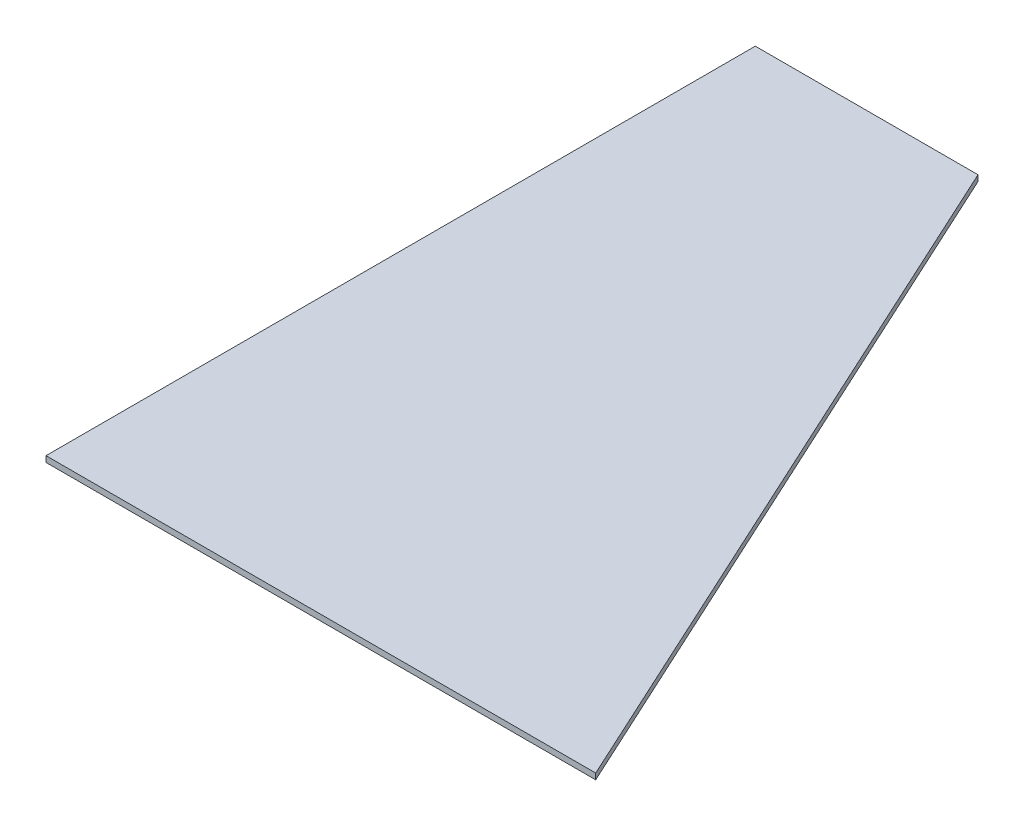
SolidWorks part; units mm, degrees
ref_plane "Front Plane" through (0, 0, 0) normal (0, 0, 1) x (1, 0, 0)
ref_plane "Top Plane" through (0, 0, 0) normal (0, 1, 0) x (1, 0, 0)
ref_plane "Right Plane" through (0, 0, 0) normal (1, 0, 0) x (0, 0, -1)
sketch "Sketch1" plane through (0, 0, 0) normal (0, 1, 0) x (1, 0, 0)
  line L0 (0, 0) -> (590.55, 0)
  line L1 (590.55, 0) -> (239.2632, 762)
  line L2 (239.2632, 762) -> (0, 762)
  line L3 (0, 762) -> (0, 0)
  dimension "D1" = 590.55
  dimension "D2" = 762
  dimension "D3" = 65.25
extrude "Boss-Extrude1" add sketch "Sketch1" along normal blind 6.35
sketch "Strut outline" plane through (0, 6.35, 0) normal (0, 1, 0) x (1, 0, 0)
  line L0 (44.45, 0) -> (44.45, 762)
  line L1 (44.45, 0) -> (-44.45, 0)
  line L2 (44.45, 762) -> (-44.45, 762)
  line L3 (-44.45, 0) -> (-44.45, 762)
  line L4 (0, 0) -> (590.55, 0) construction
  line L5 (239.2632, 762) -> (0, 762) construction
  point P8 (0, 762)
  dimension "D1" = 88.9
sketch "Sketch3" [suppressed] plane through (0, 6.35, 0) normal (0, 1, 0) x (1, 0, 0)
  line L0 (127, 330.2) -> (203.2, 330.2) construction
  line L1 (82.55, 304.8) -> (171.45, 304.8) construction
  line L2 (82.55, 304.8) -> (82.55, 381) construction
  line L3 (82.55, 381) -> (171.45, 381) construction
  line L4 (171.45, 304.8) -> (171.45, 381) construction
  line L5 (95.25, 479.425) -> (158.75, 479.425) construction
  line L6 (95.25, 479.425) -> (95.25, 536.575) construction
  line L7 (95.25, 536.575) -> (158.75, 536.575) construction
  line L8 (158.75, 479.425) -> (158.75, 536.575) construction
  line L9 (95.25, 479.425) -> (158.75, 536.575) construction
  line L10 (95.25, 536.575) -> (158.75, 479.425) construction
  line L11 (203.2, 311.15) -> (203.2, 349.25) construction
  line L12 (127, 508) -> (203.2, 508) construction
  line L13 (203.2, 488.95) -> (203.2, 527.05) construction
  line L14 (0, 762) -> (0, 0) construction
  line L15 (-50.8, 679.45) -> (37.3063, 679.45)
  line L16 (-50.8, 679.45) -> (-50.8, 685.8)
  line L17 (-50.8, 685.8) -> (50.8, 685.8)
  line L18 (50.8, 679.45) -> (50.8, 685.8)
  line L19 (-50.8, 679.45) -> (50.8, 685.8) construction
  line L20 (-50.8, 685.8) -> (38.0326, 680.248) construction
  line L21 (38.0326, 680.248) -> (50.8, 679.45) construction
  line L22 (42.0687, 679.45) -> (50.8, 679.45)
  line L23 (50.8, 679.45) -> (50.8, 609.6) construction
  line L24 (50.8, 609.6) -> (-50.8, 609.6) construction
  line L25 (-50.8, 609.6) -> (-50.8, 679.45) construction
  line L26 (63.5, 120.65) -> (114.3, 120.65) construction
  line L27 (165.1, 158.75) -> (215.9, 158.75) construction
  line L29 (165.1, 120.65) -> (165.1, 158.75) construction
  line L30 (590.55, 0) -> (239.2632, 762) construction
  line L31 (366.1278, 304.8) -> (302.3241, 443.201) construction
  circle A0 centre (127, 330.2) radius 25.4
  circle A1 centre (127, 508) radius 25.4
  circle A2 centre (203.2, 311.15) radius 3.81
  circle A3 centre (203.2, 349.25) radius 2.667
  circle A4 centre (203.2, 488.95) radius 3.81
  circle A5 centre (203.2, 527.05) radius 2.667
  circle A6 centre (381, 139.7) radius 36.5125
  arc A7 (37.3063, 679.45) -> (42.0687, 679.45) centre (39.6875, 676.275) ccw
  circle A8 centre (63.5, 120.65) radius 3.81
  circle A9 centre (114.3, 120.65) radius 3.81
  circle A10 centre (165.1, 120.65) radius 3.81
  circle A11 centre (215.9, 120.65) radius 3.81
  circle A12 centre (266.7, 120.65) radius 3.81
  circle A13 centre (165.1, 158.75) radius 2.667
  circle A14 centre (215.9, 158.75) radius 2.667
  circle A15 centre (266.7, 158.75) radius 2.667
  circle A18 centre (63.5, 158.75) radius 2.667
  circle A19 centre (114.3, 158.75) radius 2.667
  circle A21 centre (366.1278, 304.8) radius 25.4
  circle A22 centre (302.3241, 443.201) radius 25.4
  point P6 (127, 304.8)
  point P21 (0, 682.625)
  point P25 (203.2, 330.2)
  point P29 (203.2, 508)
  point P37 (0, 609.6)
  dimension "D1" = 50.8
  dimension "D4" = 50.8
  dimension "D7" = 7.62
  dimension "D8" = 5.334
  dimension "D11" = 73.025
  dimension "D14" = 7.9375
  dimension "D24" = 7.62
  dimension "D29" = 5.334
  dimension "D35" = 50.8
  dimension "D2" = 88.9
  dimension "D3" = 76.2
  dimension "D5" = 63.5
  dimension "D6" = 57.15
  dimension "D9" = 38.1
  dimension "D10" = 76.2
  dimension "D12" = 101.6
  dimension "D13" = 6.35
  dimension "D15" = 11.1125
  dimension "D16" = 9.525
  dimension "D17" = 76.2
  dimension "D18" = 177.8
  dimension "D19" = 127
  dimension "D20" = 330.2
  dimension "D21" = 609.6
  dimension "D22" = 381
  dimension "D23" = 139.7
  dimension "D26" = 50.8
  dimension "D27" = 63.5
  dimension "D28" = 120.65
  dimension "D30" = 38.1
  dimension "D32" = 50.8
  dimension "D36" = 304.8
  dimension "D37" = 76.2
  dimension "D39" = 152.4
  dimension "D25" = 5
  dimension "D31" = 3
  dimension "D38" = 2
extrude "1st_doctor_left" [suppressed] cut sketch "Sketch3" against normal through all
sketch "Sketch4" [suppressed] plane through (0, 0, 0) normal (0, -1, 0) x (1, 0, 0)
  line L0 (317.5, -139.7) -> (348.4933, -70.0878) construction
  line L1 (317.5, -139.7) -> (317.5, 0) construction
  line L2 (0, 0) -> (590.55, 0) construction
  line L3 (317.5, -139.7) -> (348.4933, -70.0878) construction
  line L4 (317.5, -139.7) -> (374.1276, -88.7122) construction
  line L5 (88.9, -158.75) -> (88.9, -196.85) construction
  line L6 (88.9, -120.65) -> (139.7, -120.65) construction
  line L7 (0, -762) -> (0, 0) construction
  line L8 (50.8, -685.8) -> (-50.8, -685.8)
  line L9 (50.8, -685.8) -> (50.8, -679.45)
  line L10 (50.8, -679.45) -> (42.0688, -679.45)
  line L11 (-50.8, -685.8) -> (-50.8, -679.45)
  line L12 (50.8, -685.8) -> (-50.8, -679.45) construction
  line L13 (50.8, -679.45) -> (-50.8, -685.8) construction
  line L14 (50.8, -679.45) -> (50.8, -609.6) construction
  line L15 (50.8, -609.6) -> (-50.8, -609.6) construction
  line L16 (-50.8, -609.6) -> (-50.8, -679.45) construction
  line L17 (37.3063, -679.45) -> (-50.8, -679.45)
  line L18 (590.55, 0) -> (239.2632, -762) construction
  line L19 (366.1278, -304.8) -> (302.3241, -443.201) construction
  line L20 (139.7, -419.1) -> (139.7, -330.2) construction
  line L21 (203.2, -330.2) -> (76.2, -330.2) construction
  circle A0 centre (139.7, -419.1) radius 7.9375
  circle A1 centre (139.7, -419.1) radius 34.925 construction
  circle A2 centre (317.5, -139.7) radius 4.7625
  circle A3 centre (317.5, -139.7) radius 50.8 construction
  circle A4 centre (348.4933, -70.0878) radius 2.667
  circle A5 centre (374.1276, -88.7122) radius 2.667
  circle A6 centre (389.9705, -116.1529) radius 2.667
  circle A7 centre (393.2826, -147.6651) radius 2.667
  circle A8 centre (383.4911, -177.8) radius 2.667
  circle A9 centre (362.2892, -201.3471) radius 2.667
  circle A10 centre (333.3429, -214.2348) radius 2.667
  circle A11 centre (301.6571, -214.2348) radius 2.667
  circle A12 centre (272.7108, -201.3471) radius 2.667
  circle A13 centre (251.5089, -177.8) radius 2.667
  circle A14 centre (241.7174, -147.6651) radius 2.667
  circle A15 centre (245.0295, -116.1529) radius 2.667
  circle A16 centre (260.8724, -88.7122) radius 2.667
  circle A17 centre (286.5067, -70.0878) radius 2.667
  circle A18 centre (88.9, -120.65) radius 3.81
  circle A19 centre (88.9, -158.75) radius 2.667
  circle A20 centre (88.9, -196.85) radius 2.667
  arc A28 (42.0688, -679.45) -> (37.3063, -679.45) centre (39.6875, -676.275) ccw
  circle A29 centre (139.7, -120.65) radius 3.81
  circle A30 centre (139.7, -120.65) radius 3.81 [skipped]
  circle A31 centre (139.7, -158.75) radius 2.667 [skipped]
  circle A32 centre (139.7, -196.85) radius 2.667 [skipped]
  circle A33 centre (139.7, -158.75) radius 2.667
  circle A34 centre (139.7, -196.85) radius 2.667
  circle A39 centre (228.6, -584.2) radius 11.1125
  circle A40 centre (366.1278, -304.8) radius 25.4
  circle A41 centre (302.3241, -443.201) radius 25.4
  circle A42 centre (203.2, -330.2) radius 2.667
  circle A43 centre (139.7, -330.2) radius 2.667
  circle A44 centre (76.2, -330.2) radius 2.667
  point P40 (0, -682.625)
  point P87 (139.7, -330.2)
  dimension "D1" = 15.875
  dimension "D4" = 69.85
  dimension "D5" = 9.525
  dimension "D8" = 101.6
  dimension "D9" = 5.334
  dimension "D14" = 7.62
  dimension "D15" = 5.334
  dimension "D25" = 7.9375
  dimension "D33" = 76.2
  dimension "D36" = 22.225
  dimension "D31" = 50.8
  dimension "D35" = 5.334
  dimension "D2" = 139.7
  dimension "D3" = 419.1
  dimension "D6" = 317.5
  dimension "D7" = 139.7
  dimension "D10" = 24
  dimension "D12" = 24
  dimension "D13" = 76.2
  dimension "D16" = 38.1
  dimension "D17" = 120.65
  dimension "D18" = 88.9
  dimension "D20" = 38.1
  dimension "D22" = 2
  dimension "D23" = 101.6
  dimension "D24" = 6.35
  dimension "D26" = 11.1125
  dimension "D27" = 9.525
  dimension "D28" = 76.2
  dimension "D29" = 609.6
  dimension "D30" = 50.8
  dimension "D32" = 304.8
  dimension "D37" = 584.2
  dimension "D38" = 228.6
  dimension "D34" = 152.4
  dimension "D39" = 127
  dimension "D40" = 88.9
  dimension "D19" = 2
  dimension "D21" = 2
  dimension "D11" = 14
extrude "1st_doctor_right" [suppressed] cut sketch "Sketch4" against normal through all
sketch "Sketch5" [suppressed] plane through (0, 6.35, 0) normal (0, 1, 0) x (1, 0, 0)
  line L0 (0, 0) -> (590.55, 0) construction
  line L1 (590.55, 0) -> (239.2632, 762) construction
  line L2 (499.483, 76.2) -> (483.5321, 110.8003) construction
  circle A0 centre (499.483, 76.2) radius 3.937
  circle A1 centre (483.5321, 110.8003) radius 3.937
  circle A2 centre (467.5811, 145.4005) radius 3.937
  circle A3 centre (451.6302, 180.0008) radius 3.937
  circle A4 centre (435.6793, 214.601) radius 3.937
  circle A5 centre (419.7283, 249.2013) radius 3.937
  circle A6 centre (403.7774, 283.8015) radius 3.937
  circle A7 centre (387.8265, 318.4018) radius 3.937
  circle A8 centre (371.8755, 353.002) radius 3.937
  circle A9 centre (355.9246, 387.6023) radius 3.937
  circle A10 centre (339.9736, 422.2025) radius 3.937
  circle A11 centre (324.0227, 456.8028) radius 3.937
  circle A12 centre (308.0718, 491.4031) radius 3.937
  circle A13 centre (292.1208, 526.0033) radius 3.937
  circle A14 centre (276.1699, 560.6036) radius 3.937
  circle A15 centre (260.219, 595.2038) radius 3.937
  circle A16 centre (244.268, 629.8041) radius 3.937
  circle A17 centre (228.3171, 664.4043) radius 3.937
  circle A18 centre (212.3662, 699.0046) radius 3.937
  circle A19 centre (196.4152, 733.6048) radius 3.937
  circle A22 centre (298.2981, 183.5005) radius 2.4384
  circle A23 centre (282.3472, 218.1008) radius 2.4384
  circle A24 centre (266.3963, 252.701) radius 4.075
  circle A25 centre (228.2963, 252.701) radius 2.4384
  circle A26 centre (190.1963, 252.701) radius 2.4384
  circle A27 centre (152.0963, 252.701) radius 2.4384
  circle A28 centre (104.2434, 356.5018) radius 2.4384
  circle A29 centre (142.3434, 356.5018) radius 2.4384
  circle A30 centre (180.4434, 356.5018) radius 2.4384
  circle A31 centre (218.5434, 356.5018) radius 4.075
  circle A32 centre (234.4944, 321.9015) radius 2.4384
  circle A33 centre (250.4453, 287.3013) radius 2.4384
  circle A34 centre (56.3906, 460.3025) radius 2.4384
  circle A35 centre (94.4906, 460.3025) radius 2.4384
  circle A36 centre (132.5906, 460.3025) radius 2.4384
  circle A37 centre (170.6906, 460.3025) radius 4.075
  circle A38 centre (186.6416, 425.7023) radius 2.4384
  circle A39 centre (202.5925, 391.102) radius 2.4384
  circle A40 centre (142.3434, 614.8842) radius 4.2
  circle A41 centre (314.2491, 148.9003) radius 5.4401
  circle A42 centre (142.3434, 640.2842) radius 2.4384
  circle A43 centre (166.5003, 622.7332) radius 2.4384
  circle A44 centre (157.2732, 594.3351) radius 2.4384
  circle A45 centre (127.4137, 594.3351) radius 2.4384
  circle A46 centre (118.1866, 622.7332) radius 2.4384
  point P97 (142.3434, 614.8842)
  dimension "D3" = 7.874
  dimension "D5" = 8.4
  dimension "D9" = 8.15
  dimension "D12" = 4.8768
  dimension "D15" = 38.1
  dimension "D8" = 4.8768
  dimension "D1" = 76.2
  dimension "D2" = 50.8
  dimension "D6" = 38.1
  dimension "D7" = 25.4
  dimension "D10" = 38.1
  dimension "D11" = 38.1
  dimension "D13" = 38.1
  dimension "D17" = 38.1
  dimension "D4" = 20
  dimension "D14" = 3
  dimension "D18" = 3
  dimension "D16" = 5
extrude "13th_doctor" [suppressed] cut sketch "Sketch5" against normal through all
sketch "Sketch6" [suppressed] plane through (0, 0, 0) normal (0, -1, 0) x (1, 0, 0)
  line L0 (0, -12.7) -> (230.9812, -12.7)
  line L1 (0, -762) -> (0, 0) construction
  line L2 (230.9812, -12.7) -> (230.9812, -190.5)
  line L3 (230.9812, -190.5) -> (180.975, -190.5)
  line L4 (180.975, -190.5) -> (180.975, -373.0625)
  line L5 (180.975, -373.0625) -> (141.2875, -373.0625)
  line L6 (141.2875, -373.0625) -> (141.2875, -558.8)
  line L7 (141.2875, -558.8) -> (0, -558.8)
  line L8 (0, 0) -> (590.55, 0) construction
  line L9 (239.2632, -762) -> (0, -762) construction
  line L10 (-230.9813, -12.7) -> (230.9812, -12.7) construction
  line L11 (-180.975, -190.5) -> (180.975, -190.5) construction
  line L12 (-141.2875, -373.0625) -> (141.2875, -373.0625) construction
  line L13 (0, -558.8) -> (0, -12.7)
  point P17 (0, -12.7)
  point P19 (0, -190.5)
  point P22 (0, -373.0625)
  dimension "D1" = 12.7
  dimension "D2" = 190.5
  dimension "D3" = 373.0625
  dimension "D4" = 203.2
  dimension "D5" = 461.9625
  dimension "D6" = 361.95
  dimension "D7" = 282.575
extrude "5th_doctor_TV_cutout" [suppressed] cut sketch "Sketch6" against normal through all
sketch "Sketch7" [suppressed] plane through (0, 6.35, 0) normal (0, 1, 0) x (1, 0, 0)
  line L0 (219.075, 421.8299) -> (288.925, 421.8299) construction
  line L1 (309.5625, 112.5728) -> (350.8375, 112.5728)
  line L2 (309.5625, 112.5728) -> (309.5625, 90.6272)
  line L3 (309.5625, 90.6272) -> (350.8375, 90.6272)
  line L4 (350.8375, 112.5728) -> (350.8375, 90.6272)
  line L5 (309.5625, 112.5728) -> (350.8375, 90.6272) construction
  line L6 (309.5625, 90.6272) -> (350.8375, 112.5728) construction
  line L7 (309.5625, 188.7728) -> (350.8375, 188.7728)
  line L8 (309.5625, 188.7728) -> (309.5625, 166.8272)
  line L9 (309.5625, 166.8272) -> (350.8375, 166.8272)
  line L10 (350.8375, 188.7728) -> (350.8375, 166.8272)
  line L11 (309.5625, 188.7728) -> (350.8375, 166.8272) construction
  line L12 (309.5625, 166.8272) -> (350.8375, 188.7728) construction
  line L13 (288.925, 421.8299) -> (310.5098, 488.2612) construction
  line L14 (310.5098, 488.2612) -> (254, 529.318) construction
  line L15 (254, 529.318) -> (197.4902, 488.2612) construction
  line L16 (197.4902, 488.2612) -> (219.075, 421.8299) construction
  line L17 (197.4902, 488.2612) -> (254, 469.9) construction
  line L18 (254, 469.9) -> (254, 529.318) construction
  line L19 (310.5098, 488.2612) -> (254, 469.9) construction
  line L20 (254, 469.9) -> (288.925, 421.8299) construction
  line L21 (254, 469.9) -> (219.075, 421.8299) construction
  line L22 (234.95, 292.1) -> (285.75, 292.1) construction
  line L32 (400.05, 215.9) -> (438.15, 215.9) construction
  line L33 (400.05, 215.9) -> (400.05, 177.8) construction
  line L34 (400.05, 177.8) -> (438.15, 177.8) construction
  line L35 (438.15, 215.9) -> (438.15, 177.8) construction
  line L36 (400.05, 177.8) -> (438.15, 177.8) construction
  line L37 (400.05, 177.8) -> (400.05, 139.7) construction
  line L38 (400.05, 139.7) -> (438.15, 139.7) construction
  line L39 (438.15, 177.8) -> (438.15, 139.7) construction
  line L40 (400.05, 139.7) -> (438.15, 139.7) construction
  line L41 (400.05, 139.7) -> (400.05, 101.6) construction
  line L42 (400.05, 101.6) -> (438.15, 101.6) construction
  line L43 (438.15, 139.7) -> (438.15, 101.6) construction
  line L44 (400.05, 101.6) -> (438.15, 101.6) construction
  line L45 (400.05, 101.6) -> (400.05, 63.5) construction
  line L46 (400.05, 63.5) -> (438.15, 63.5) construction
  line L47 (438.15, 101.6) -> (438.15, 63.5) construction
  circle A0 centre (254, 469.9) radius 4.572
  circle A1 centre (254, 469.9) radius 59.418 construction
  circle A2 centre (254, 469.9) radius 72.118 construction
  circle A3 centre (238.125, 399.551) radius 2.4384
  circle A4 centre (269.875, 399.551) radius 2.4384
  circle A5 centre (191.9998, 433.0629) radius 2.4384
  circle A6 centre (182.1885, 463.259) radius 2.4384
  circle A7 centre (199.8067, 517.4825) radius 2.4384
  circle A8 centre (225.493, 536.1446) radius 2.4384
  circle A9 centre (282.507, 536.1446) radius 2.4384
  circle A10 centre (308.1933, 517.4825) radius 2.4384
  circle A11 centre (325.8115, 463.259) radius 2.4384
  circle A12 centre (316.0002, 433.0629) radius 2.4384
  circle A13 centre (234.95, 292.1) radius 3.937
  circle A14 centre (285.75, 292.1) radius 3.937
  circle A15 centre (336.55, 292.1) radius 3.937
  circle A16 centre (387.35, 292.1) radius 3.937
  circle A17 centre (400.05, 215.9) radius 3.937
  circle A18 centre (438.15, 215.9) radius 3.937
  circle A19 centre (400.05, 177.8) radius 3.937
  circle A20 centre (438.15, 139.7) radius 3.937
  circle A21 centre (438.15, 101.6) radius 3.937
  circle A22 centre (438.15, 63.5) radius 3.937
  circle A23 centre (400.05, 63.5) radius 3.937
  circle A24 centre (438.15, 177.8) radius 2.4384
  circle A25 centre (400.05, 139.7) radius 2.4384
  circle A26 centre (400.05, 101.6) radius 2.4384
  point P0 (330.2, 101.6)
  point P5 (330.2, 177.8)
  point P43 (254, 469.9)
  point P69 (419.1, 101.6)
  point P75 (254, 542.018)
  dimension "D6" = 9.144
  dimension "D10" = 12.7
  dimension "D11" = 4.8768
  dimension "D14" = 7.874
  dimension "D1" = 41.275
  dimension "D2" = 21.9456
  dimension "D3" = 76.2
  dimension "D4" = 330.2
  dimension "D5" = 101.6
  dimension "D7" = 254
  dimension "D8" = 469.9
  dimension "D9" = 69.85
  dimension "D12" = 31.75
  dimension "D15" = 234.95
  dimension "D16" = 292.1
  dimension "D18" = 50.8
  dimension "D19" = 38.1
  dimension "D20" = 88.9
  dimension "D17" = 4
  dimension "D13" = 5
extrude "5th_doctor_left" [suppressed] cut sketch "Sketch7" against normal through all
sketch "Sketch8" [suppressed] plane through (0, 0, 0) normal (0, -1, 0) x (1, 0, 0)
  line L0 (406.527, -156.3878) -> (393.8058, -156.3878) construction
  line L1 (406.527, -130.9878) -> (330.2, -130.9878)
  line L2 (406.527, -130.9878) -> (406.527, -101.6)
  line L3 (406.527, -101.6) -> (330.2, -101.6)
  line L4 (330.2, -130.9878) -> (330.2, -101.6)
  line L5 (393.8058, -156.3878) -> (381.0847, -156.3878) construction
  line L6 (381.0847, -156.3878) -> (368.3635, -156.3878) construction
  line L7 (368.3635, -156.3878) -> (355.6423, -156.3878) construction
  line L8 (355.6423, -156.3878) -> (342.9212, -156.3878) construction
  line L9 (342.9212, -156.3878) -> (330.2, -156.3878) construction
  line L10 (400.1664, -156.3878) -> (387.4664, -156.3878) construction
  line L11 (400.1664, -156.3878) -> (400.1664, -181.7878) construction
  line L12 (387.4664, -207.1878) -> (387.4664, -232.5878) construction
  line L13 (247.65, -355.6) -> (285.75, -355.6) construction
  line L14 (262.5725, -529.717) -> (232.7275, -529.717)
  line L15 (262.5725, -529.717) -> (262.5725, -508)
  line L16 (262.5725, -508) -> (232.7275, -508)
  line L17 (232.7275, -529.717) -> (232.7275, -508)
  line L18 (247.65, -393.7) -> (247.65, -355.6) construction
  line L19 (247.65, -469.9) -> (285.75, -469.9) construction
  line L20 (247.65, -469.9) -> (247.65, -508) construction
  line L21 (361.95, -355.6) -> (247.65, -355.6) construction
  line L22 (355.6, -304.8) -> (254, -304.8) construction
  circle A0 centre (400.1664, -156.3878) radius 2.4384
  circle A1 centre (387.4664, -156.3878) radius 2.4384
  circle A2 centre (374.7664, -156.3878) radius 2.4384
  circle A3 centre (362.0664, -156.3878) radius 2.4384
  circle A4 centre (349.3664, -156.3878) radius 2.4384
  circle A5 centre (336.6664, -156.3878) radius 2.4384
  circle A6 centre (387.4664, -181.7878) radius 2.4384
  circle A7 centre (374.7664, -181.7878) radius 2.4384
  circle A8 centre (362.0664, -181.7878) radius 2.4384
  circle A9 centre (349.3664, -181.7878) radius 2.4384
  circle A10 centre (336.6664, -181.7878) radius 2.4384
  circle A11 centre (387.4664, -207.1878) radius 2.4384
  circle A12 centre (374.7664, -207.1878) radius 2.4384
  circle A13 centre (362.0664, -207.1878) radius 2.4384
  circle A14 centre (349.3664, -207.1878) radius 2.4384
  circle A15 centre (336.6664, -207.1878) radius 2.4384
  circle A16 centre (400.1664, -181.7878) radius 2.4384
  circle A17 centre (400.1664, -207.1878) radius 2.4384
  circle A18 centre (387.4664, -232.5878) radius 2.4384
  circle A19 centre (374.7664, -232.5878) radius 2.4384
  circle A20 centre (362.0664, -232.5878) radius 2.4384
  circle A21 centre (349.3664, -232.5878) radius 2.4384
  circle A22 centre (336.6664, -232.5878) radius 2.4384
  circle A23 centre (355.6, -304.8) radius 11.1125
  circle A24 centre (254, -304.8) radius 8.5725
  circle A25 centre (247.65, -355.6) radius 3.937
  circle A26 centre (285.75, -355.6) radius 3.937
  circle A27 centre (323.85, -355.6) radius 3.937
  circle A28 centre (361.95, -355.6) radius 3.937
  circle A29 centre (247.65, -393.7) radius 3.937
  circle A30 centre (247.65, -431.8) radius 3.937
  circle A31 centre (247.65, -469.9) radius 3.937
  circle A33 centre (285.75, -469.9) radius 3.937
  point P75 (304.8, -304.8)
  point P93 (304.8, -355.6)
  dimension "D6" = 4.8768
  dimension "D12" = 17.145
  dimension "D13" = 22.225
  dimension "D21" = 7.874
  dimension "D1" = 29.3878
  dimension "D2" = 76.327
  dimension "D3" = 101.6
  dimension "D4" = 330.2
  dimension "D5" = 25.4
  dimension "D9" = 12.7
  dimension "D10" = 25.4
  dimension "D14" = 101.6
  dimension "D15" = 254
  dimension "D16" = 304.8
  dimension "D17" = 21.717
  dimension "D18" = 29.845
  dimension "D19" = 508
  dimension "D23" = 355.6
  dimension "D25" = 38.1
  dimension "D27" = 38.1
  dimension "D29" = 38.1
  dimension "D7" = 6
  dimension "D8" = 3
  dimension "D11" = 2
  dimension "D24" = 4
  dimension "D26" = 4
  dimension "D28" = 2
extrude "5th_doctor_right" [suppressed] cut sketch "Sketch8" against normal through all
sketch "Sketch9" [suppressed] plane through (0, 6.35, 0) normal (0, 1, 0) x (1, 0, 0)
  line L0 (228.9969, 733.425) -> (228.9969, 581.025)
  line L1 (228.9969, 581.025) -> (228.9969, 568.325) construction
  line L2 (228.9969, 733.425) -> (228.9969, 748.411) construction
  line L4 (0, 558.8) -> (141.2875, 558.8) construction
  line L5 (-228.9969, 568.325) -> (228.9969, 568.325) construction
  line L7 (0, 762) -> (0, 558.8) construction
  line L8 (228.9969, 581.025) -> (127.3969, 568.325)
  line L9 (127.3969, 568.325) -> (0, 568.325)
  line L10 (228.9969, 733.425) -> (102.8841, 748.411)
  line L11 (102.8841, 748.411) -> (0, 748.411)
  line L12 (0, 748.411) -> (0, 568.325)
  point P11 (0, 568.325)
  dimension "D1" = 12.7
  dimension "D2" = 152.4
  dimension "D3" = 14.986
  dimension "D4" = 9.525
  dimension "D5" = 457.9937
  dimension "D6" = 101.6
  dimension "D7" = 127
  dimension "D8" = 180.086
extrude "5th_doctor_keys_cutout" [suppressed] cut sketch "Sketch9" against normal through all
sketch "Sketch10" [suppressed] plane through (0, 6.35, 0) normal (0, 1, 0) x (1, 0, 0)
  line L0 (0, 0) -> (590.55, 0) construction
  line L1 (590.55, 0) -> (239.2632, 762) construction
  line L2 (499.483, 76.2) -> (483.5321, 110.8003) construction
  circle A0 centre (499.483, 76.2) radius 3.937
  circle A1 centre (483.5321, 110.8003) radius 3.937
  circle A2 centre (467.5811, 145.4005) radius 3.937
  circle A3 centre (451.6302, 180.0008) radius 3.937
  circle A4 centre (435.6793, 214.601) radius 3.937
  circle A5 centre (419.7283, 249.2013) radius 3.937
  circle A6 centre (403.7774, 283.8015) radius 3.937
  circle A7 centre (387.8265, 318.4018) radius 3.937
  circle A8 centre (371.8755, 353.002) radius 3.937
  circle A9 centre (355.9246, 387.6023) radius 3.937
  circle A10 centre (339.9736, 422.2025) radius 3.937
  circle A11 centre (324.0227, 456.8028) radius 3.937
  circle A12 centre (308.0718, 491.4031) radius 3.937
  circle A13 centre (292.1208, 526.0033) radius 3.937
  circle A14 centre (276.1699, 560.6036) radius 3.937
  circle A15 centre (260.219, 595.2038) radius 3.937
  circle A16 centre (244.268, 629.8041) radius 3.937
  circle A17 centre (228.3171, 664.4043) radius 3.937
  circle A18 centre (212.3662, 699.0046) radius 3.937
  circle A19 centre (196.4152, 733.6048) radius 3.937
  dimension "D1" = 7.874
  dimension "D2" = 76.2
  dimension "D3" = 50.8
  dimension "D5" = 38.1
  dimension "D4" = 20
extrude "10th_doctor_side_LEDs" [suppressed] cut sketch "Sketch10" against normal through all
sketch "Sketch11" [suppressed] plane through (0, 6.35, 0) normal (0, 1, 0) x (1, 0, 0)
  line L0 (57.15, 635) -> (132.5735, 607.5481)
  line L1 (139.7, 295.275) -> (333.375, 295.275)
  line L2 (139.7, 295.275) -> (139.7, 76.2)
  line L3 (139.7, 76.2) -> (333.375, 76.2)
  line L4 (333.375, 295.275) -> (333.375, 76.2)
  line L5 (57.15, 635) -> (84.515, 710.1848)
  line L6 (132.5735, 607.5481) -> (159.9385, 682.7329)
  line L7 (84.515, 710.1848) -> (159.9385, 682.7329)
  line L8 (239.2632, 762) -> (0, 762) construction
  line L9 (196.2955, 460.8504) -> (277.0295, 498.0692) construction
  line L10 (590.55, 0) -> (239.2632, 762) construction
  line L11 (277.0295, 498.0692) -> (245.1276, 567.2697) construction
  line L12 (292.1208, 526.0033) -> (308.0718, 491.4031) construction
  line L13 (300.0963, 508.7032) -> (277.0295, 498.0692) construction
  line L14 (196.2955, 460.8504) -> (277.0295, 498.0692) construction
  line L15 (196.2955, 460.8504) -> (277.3512, 424.3375) construction
  circle A0 centre (196.2955, 460.8504) radius 6.35
  circle A1 centre (196.2955, 460.8504) radius 50.8 construction
  circle A2 centre (196.2955, 460.8504) radius 57.531 construction
  circle A3 centre (277.0295, 498.0692) radius 2.4384
  circle A4 centre (245.1276, 567.2697) radius 2.4384
  circle A5 centre (213.2257, 636.4702) radius 2.4384
  circle A6 centre (181.3239, 705.6708) radius 2.4384
  circle A7 centre (277.3512, 424.3375) radius 2.4384
  circle A8 centre (221.9162, 375.7223) radius 2.4384
  circle A9 centre (148.8572, 385.6652) radius 2.4384
  circle A10 centre (108.4302, 447.3266) radius 2.4384
  circle A11 centre (128.4442, 518.2908) radius 2.4384
  dimension "D10" = 12.7
  dimension "D13" = 101.6
  dimension "D14" = 115.062
  dimension "D15" = 4.8768
  dimension "D1" = 219.075
  dimension "D2" = 193.675
  dimension "D3" = 139.7
  dimension "D4" = 76.2
  dimension "D5" = 80.264
  dimension "D6" = 80.01
  dimension "D7" = 20
  dimension "D8" = 57.15
  dimension "D9" = 635
  dimension "D11" = 25.4
  dimension "D12" = 6
  dimension "D16" = 88.9
  dimension "D18" = 76.2
  dimension "D19" = 49
  dimension "D17" = 4
extrude "10th_doctor_left" [suppressed] cut sketch "Sketch11" against normal through all
sketch "Sketch13" [suppressed] plane through (0, 0, 0) normal (0, -1, 0) x (1, 0, 0)
  line L0 (159.6998, -682.8198) -> (132.3348, -607.635)
  line L1 (159.6998, -682.8198) -> (84.515, -710.1848)
  line L2 (132.3348, -607.635) -> (57.15, -635)
  line L3 (84.515, -710.1848) -> (57.15, -635)
  line L4 (239.2632, -762) -> (0, -762) construction
  line L5 (367.099, -156.9981) -> (344.5108, -72.6975) construction
  line L6 (0, 0) -> (590.55, 0) construction
  line L7 (467.5811, -145.4005) -> (451.6302, -180.0008) construction
  line L8 (459.6057, -162.7006) -> (436.5388, -152.0667) construction
  line L9 (436.5388, -152.0667) -> (355.8049, -114.8478) construction
  line L10 (436.5388, -152.0667) -> (468.4407, -82.8662) construction
  line L11 (355.8049, -114.8478) -> (436.5388, -152.0667) construction
  line L12 (355.8049, -114.8478) -> (380.6817, -200.1963) construction
  circle A0 centre (344.5108, -72.6975) radius 2.3495
  circle A1 centre (367.099, -156.9981) radius 2.3495
  circle A2 centre (355.8049, -114.8478) radius 50.8 construction
  circle A3 centre (436.5388, -152.0667) radius 2.4384
  circle A4 centre (468.4407, -82.8662) radius 2.4384
  circle A5 centre (380.6817, -200.1963) radius 2.4384
  circle A6 centre (307.7123, -189.6162) radius 2.4384
  circle A7 centre (267.8249, -127.6043) radius 2.4384
  circle A8 centre (288.4574, -56.8175) radius 2.4384
  dimension "D6" = 4.699
  dimension "D7" = 101.6
  dimension "D11" = 4.8768
  dimension "D1" = 20
  dimension "D2" = 635
  dimension "D3" = 57.15
  dimension "D4" = 80.01
  dimension "D5" = 87.2744
  dimension "D8" = 75
  dimension "D9" = 25.4
  dimension "D10" = 88.9
  dimension "D13" = 76.2
  dimension "D15" = 49
  dimension "D12" = 2
  dimension "D14" = 5
extrude "10th_doctor_right" [suppressed] cut sketch "Sketch13" against normal through all
sketch "Sketch14" [suppressed] plane through (0, 0, 0) normal (0, -1, 0) x (1, 0, 0)
  line L0 (101.6, -330.2) -> (0, -330.2) construction
  line L1 (0, -762) -> (0, 0) construction
  line L2 (101.6, -330.2) -> (113.9131, -301.625) construction
  line L3 (113.9131, -301.625) -> (114.7926, -299.5839) construction
  line L4 (101.6, -330.2) -> (99.2128, -335.7401) construction
  line L5 (113.9131, -358.775) -> (101.6, -330.2) construction
  line L6 (101.6, -330.2) -> (99.2128, -324.6599) construction
  line L7 (113.9131, -358.775) -> (114.7926, -360.8161) construction
  line L8 (113.9131, -358.775) -> (113.9131, -360.9975) construction
  line L9 (113.9131, -301.625) -> (113.9131, -299.4025) construction
  line L10 (120.7866, -357.6955) -> (101.6, -330.2) construction
  line L11 (101.6, -330.2) -> (98.1479, -325.2529) construction
  line L12 (120.7866, -357.6955) -> (122.0584, -359.5181) construction
  line L13 (120.7866, -357.6955) -> (120.7866, -359.918) construction
  line L14 (120.7866, -302.7045) -> (120.7866, -300.482) construction
  line L15 (120.7866, -302.7045) -> (101.6, -330.2) construction
  line L16 (101.6, -330.2) -> (98.1479, -335.1471) construction
  line L17 (120.7866, -302.7045) -> (122.0584, -300.8819) construction
  circle A0 centre (101.6, -330.2) radius 203.2 construction
  circle A1 centre (101.6, -330.2) radius 6.0325
  circle A2 centre (113.9131, -301.625) radius 2.2225
  circle A3 centre (120.7866, -302.7045) radius 2.2225
  circle A4 centre (120.7866, -357.6955) radius 2.2225
  circle A5 centre (113.9131, -358.775) radius 2.2225
  circle A6 centre (101.6, -330.2) radius 19.05 construction
  dimension "D1" = 406.4
  dimension "D4" = 12.065
  dimension "D5" = 4.445
  dimension "D10" = 38.1
  dimension "D2" = 330.2
  dimension "D3" = 101.6
  dimension "D6" = 39.37
  dimension "D7" = 41.783
  dimension "D8" = 61.595
  dimension "D9" = 59.436
extrude "10th_doctor_motor_hole" [suppressed] cut sketch "Sketch14" against normal through all
sketch "Sketch15" [suppressed] plane through (0, 6.35, 0) normal (0, 1, 0) x (1, 0, 0)
  line L0 (50.8, 137.16) -> (50.8, 203.2)
  line L1 (76.2, 677.9768) -> (195.3768, 677.9768)
  line L2 (76.2, 677.9768) -> (76.2, 558.8)
  line L3 (76.2, 558.8) -> (195.3768, 558.8)
  line L4 (195.3768, 677.9768) -> (195.3768, 558.8)
  line L5 (50.8, 203.2) -> (105.41, 203.2)
  line L6 (105.41, 203.2) -> (105.41, 137.16)
  line L7 (105.41, 137.16) -> (88.9, 113.03)
  line L8 (88.9, 113.03) -> (67.31, 113.03)
  line L9 (67.31, 113.03) -> (50.8, 137.16)
  line L10 (78.105, 203.2) -> (78.105, 113.03) construction
  line L11 (198.501, 149.0472) -> (198.501, 168.0972) construction
  line L12 (203.2, 177.4444) -> (239.8522, 177.4444)
  line L13 (203.2, 177.4444) -> (203.2, 139.7)
  line L14 (203.2, 139.7) -> (239.8522, 139.7)
  line L15 (239.8522, 177.4444) -> (239.8522, 139.7)
  line L16 (193.04, 177.4444) -> (256.54, 177.4444) construction
  line L17 (193.04, 177.4444) -> (193.04, 139.7) construction
  line L18 (193.04, 139.7) -> (256.54, 139.7) construction
  line L19 (256.54, 177.4444) -> (256.54, 139.7) construction
  line L20 (250.7742, 149.0472) -> (250.7742, 168.0972) construction
  line L21 (152.4, 304.8) -> (196.85, 304.8) construction
  line L22 (152.4, 342.9) -> (152.4, 381) construction
  line L23 (241.3, 342.9) -> (241.3, 381) construction
  line L24 (330.2, 342.9) -> (330.2, 381) construction
  line L25 (488.95, 63.5) -> (438.15, 63.5) construction
  circle A0 centre (381, 152.4) radius 12.065
  circle A1 centre (381, 152.4) radius 48.895 construction
  circle A2 centre (78.105, 241.3) radius 2.4384
  circle A3 centre (78.105, 279.4) radius 2.4384
  circle A4 centre (78.105, 317.5) radius 2.4384
  circle A5 centre (198.501, 168.0972) radius 1.905
  circle A6 centre (198.501, 149.0472) radius 1.905
  circle A7 centre (250.7742, 149.0472) radius 1.905
  circle A8 centre (250.7742, 168.0972) radius 1.905
  circle A9 centre (152.4, 304.8) radius 2.9845
  circle A10 centre (152.4, 342.9) radius 2.4384
  circle A11 centre (196.85, 304.8) radius 2.9845
  circle A12 centre (196.85, 342.9) radius 2.4384
  circle A13 centre (241.3, 304.8) radius 2.9845
  circle A14 centre (241.3, 342.9) radius 2.4384
  circle A15 centre (285.75, 304.8) radius 2.9845
  circle A16 centre (285.75, 342.9) radius 2.4384
  circle A17 centre (330.2, 304.8) radius 2.9845
  circle A18 centre (330.2, 342.9) radius 2.4384
  circle A19 centre (152.4, 381) radius 2.4384
  circle A20 centre (196.85, 381) radius 2.4384
  circle A21 centre (152.4, 419.1) radius 2.4384
  circle A22 centre (196.85, 419.1) radius 2.4384
  circle A23 centre (152.4, 457.2) radius 2.4384
  circle A24 centre (196.85, 457.2) radius 2.4384
  circle A25 centre (241.3, 381) radius 2.4384
  circle A26 centre (285.75, 381) radius 2.4384
  circle A27 centre (241.3, 419.1) radius 2.4384
  circle A28 centre (285.75, 419.1) radius 2.4384
  circle A29 centre (330.2, 381) radius 2.4384
  circle A30 centre (488.95, 63.5) radius 2.4384
  circle A31 centre (438.15, 63.5) radius 2.4384
  circle A32 centre (387.35, 63.5) radius 2.4384
  circle A33 centre (336.55, 63.5) radius 2.4384
  circle A34 centre (285.75, 63.5) radius 2.4384
  circle A35 centre (234.95, 63.5) radius 2.4384
  point P32 (203.2, 158.5722)
  point P35 (198.501, 158.5722)
  point P40 (250.7742, 158.5722)
  dimension "D1" = 24.13
  dimension "D2" = 97.79
  dimension "D14" = 4.8768
  dimension "D26" = 3.81
  dimension "D27" = 5.969
  dimension "D40" = 6
  dimension "D3" = 381
  dimension "D4" = 152.4
  dimension "D5" = 119.1768
  dimension "D6" = 76.2
  dimension "D7" = 558.8
  dimension "D8" = 54.61
  dimension "D9" = 66.04
  dimension "D10" = 90.17
  dimension "D11" = 21.59
  dimension "D12" = 203.2
  dimension "D13" = 50.8
  dimension "D15" = 38.1
  dimension "D17" = 38.1
  dimension "D18" = 36.6522
  dimension "D19" = 37.7444
  dimension "D20" = 203.2
  dimension "D21" = 139.7
  dimension "D22" = 63.5
  dimension "D23" = 10.16
  dimension "D24" = 4.699
  dimension "D25" = 19.05
  dimension "D28" = 10.922
  dimension "D29" = 38.1
  dimension "D30" = 152.4
  dimension "D31" = 304.8
  dimension "D33" = 44.45
  dimension "D35" = 38.1
  dimension "D37" = 38.1
  dimension "D39" = 38.1
  dimension "D41" = 50.8
  dimension "D42" = 101.6
  dimension "D43" = 63.5
  dimension "D16" = 3
  dimension "D32" = 5
  dimension "D34" = 4
  dimension "D36" = 3
  dimension "D38" = 2
extrude "11th_doctor_left" [suppressed] cut sketch "Sketch15" against normal through all
sketch "Sketch16" [suppressed] plane through (0, 0, 0) normal (0, -1, 0) x (1, 0, 0)
  line L0 (76.2, -101.6) -> (101.6, -101.6) construction
  line L1 (76.2, -101.6) -> (76.2, -127) construction
  line L2 (82.0674, -636.27) -> (82.0674, -584.2) construction
  line L3 (76.2, -636.27) -> (87.9348, -636.27)
  line L4 (76.2, -636.27) -> (76.2, -584.2)
  line L5 (76.2, -584.2) -> (87.9348, -584.2)
  line L6 (87.9348, -636.27) -> (87.9348, -584.2)
  line L7 (141.7574, -592.6455) -> (149.3774, -592.6455)
  line L8 (141.7574, -592.6455) -> (141.7574, -627.8245)
  line L9 (141.7574, -627.8245) -> (149.3774, -627.8245)
  line L10 (149.3774, -592.6455) -> (149.3774, -627.8245)
  line L11 (203.6572, -602.2721) -> (214.4776, -602.2721)
  line L12 (203.6572, -602.2721) -> (203.6572, -618.1979)
  line L13 (203.6572, -618.1979) -> (214.4776, -618.1979)
  line L14 (214.4776, -602.2721) -> (214.4776, -618.1979)
  line L15 (113.8174, -629.285) -> (113.8174, -591.185) construction
  line L16 (145.5674, -627.8245) -> (145.5674, -592.6455) construction
  line L17 (177.3174, -629.285) -> (177.3174, -591.185) construction
  line L18 (209.0674, -618.1979) -> (209.0674, -602.2721) construction
  line L19 (240.8174, -629.285) -> (240.8174, -591.185) construction
  line L20 (240.8174, -610.235) -> (209.0674, -610.235) construction
  line L21 (209.0674, -610.235) -> (177.3174, -610.235) construction
  line L22 (177.3174, -610.235) -> (145.5674, -610.235) construction
  line L23 (145.5674, -610.235) -> (113.8174, -610.235) construction
  line L24 (113.8174, -610.235) -> (82.0674, -610.235) construction
  line L25 (488.95, -63.5) -> (438.15, -63.5) construction
  line L26 (211.2772, -382.524) -> (152.4, -382.524)
  line L27 (211.2772, -382.524) -> (211.2772, -342.9)
  line L28 (211.2772, -342.9) -> (152.4, -342.9)
  line L29 (152.4, -382.524) -> (152.4, -342.9)
  line L30 (488.95, -63.5) -> (403.8783, -248.0347) construction
  line L31 (590.55, 0) -> (239.2632, -762) construction
  line L32 (403.8783, -248.0347) -> (382.6104, -294.1684) construction
  circle A0 centre (381, -152.4) radius 12.065
  circle A1 centre (381, -152.4) radius 48.895 construction
  circle A2 centre (76.2, -101.6) radius 2.4384
  circle A3 centre (101.6, -101.6) radius 2.4384
  circle A4 centre (127, -101.6) radius 2.4384
  circle A5 centre (152.4, -101.6) radius 2.4384
  circle A6 centre (177.8, -101.6) radius 2.4384
  circle A7 centre (203.2, -101.6) radius 2.4384
  circle A8 centre (228.6, -101.6) radius 2.4384
  circle A9 centre (254, -101.6) radius 2.4384
  circle A10 centre (101.6, -127) radius 2.4384
  circle A11 centre (127, -127) radius 2.4384
  circle A12 centre (152.4, -127) radius 2.4384
  circle A13 centre (177.8, -127) radius 2.4384
  circle A14 centre (203.2, -127) radius 2.4384
  circle A15 centre (228.6, -127) radius 2.4384
  circle A16 centre (254, -127) radius 2.4384
  circle A17 centre (101.6, -152.4) radius 2.4384
  circle A18 centre (127, -152.4) radius 2.4384
  circle A19 centre (152.4, -152.4) radius 2.4384
  circle A20 centre (177.8, -152.4) radius 2.4384
  circle A21 centre (203.2, -152.4) radius 2.4384
  circle A22 centre (228.6, -152.4) radius 2.4384
  circle A23 centre (254, -152.4) radius 2.4384
  circle A24 centre (101.6, -177.8) radius 2.4384
  circle A25 centre (127, -177.8) radius 2.4384
  circle A26 centre (152.4, -177.8) radius 2.4384
  circle A27 centre (177.8, -177.8) radius 2.4384
  circle A28 centre (203.2, -177.8) radius 2.4384
  circle A29 centre (228.6, -177.8) radius 2.4384
  circle A30 centre (254, -177.8) radius 2.4384
  circle A31 centre (101.6, -203.2) radius 2.4384
  circle A32 centre (127, -203.2) radius 2.4384
  circle A33 centre (152.4, -203.2) radius 2.4384
  circle A34 centre (177.8, -203.2) radius 2.4384
  circle A35 centre (203.2, -203.2) radius 2.4384
  circle A36 centre (228.6, -203.2) radius 2.4384
  circle A37 centre (254, -203.2) radius 2.4384
  circle A38 centre (101.6, -228.6) radius 2.4384
  circle A39 centre (127, -228.6) radius 2.4384
  circle A40 centre (152.4, -228.6) radius 2.4384
  circle A41 centre (177.8, -228.6) radius 2.4384
  circle A42 centre (203.2, -228.6) radius 2.4384
  circle A43 centre (228.6, -228.6) radius 2.4384
  circle A44 centre (254, -228.6) radius 2.4384
  circle A45 centre (76.2, -127) radius 2.4384
  circle A46 centre (76.2, -152.4) radius 2.4384
  circle A47 centre (76.2, -177.8) radius 2.4384
  circle A48 centre (76.2, -203.2) radius 2.4384
  circle A49 centre (76.2, -228.6) radius 2.4384
  circle A50 centre (88.9, -50.8) radius 1.7272
  circle A51 centre (113.8174, -591.185) radius 2.9845
  circle A52 centre (177.3174, -591.185) radius 2.9845
  circle A53 centre (240.8174, -591.185) radius 2.9845
  circle A54 centre (240.8174, -629.285) radius 2.4384
  circle A55 centre (177.3174, -629.285) radius 2.4384
  circle A56 centre (113.8174, -629.285) radius 2.4384
  circle A57 centre (488.95, -63.5) radius 2.4384
  circle A58 centre (438.15, -63.5) radius 2.4384
  circle A59 centre (387.35, -63.5) radius 2.4384
  circle A60 centre (336.55, -63.5) radius 2.4384
  circle A61 centre (403.8783, -248.0347) radius 2.4384
  circle A62 centre (382.6104, -294.1684) radius 2.4384
  circle A63 centre (361.3425, -340.302) radius 2.4384
  dimension "D1" = 24.13
  dimension "D4" = 97.79
  dimension "D5" = 4.8768
  dimension "D12" = 3.4544
  dimension "D16" = 5.969
  dimension "D17" = 4.8768
  dimension "D2" = 381
  dimension "D3" = 152.4
  dimension "D8" = 25.4
  dimension "D9" = 25.4
  dimension "D10" = 101.6
  dimension "D11" = 76.2
  dimension "D13" = 88.9
  dimension "D14" = 50.8
  dimension "D15" = 11.7348
  dimension "D18" = 52.07
  dimension "D19" = 35.179
  dimension "D20" = 7.62
  dimension "D21" = 15.9258
  dimension "D22" = 10.8204
  dimension "D23" = 38.1
  dimension "D24" = 31.75
  dimension "D25" = 584.2
  dimension "D26" = 76.2
  dimension "D27" = 58.8772
  dimension "D28" = 39.624
  dimension "D29" = 342.9
  dimension "D30" = 152.4
  dimension "D31" = 101.6
  dimension "D32" = 63.5
  dimension "D34" = 50.8
  dimension "D35" = 203.2
  dimension "D37" = 50.8
  dimension "D6" = 8
  dimension "D7" = 6
  dimension "D33" = 4
  dimension "D36" = 3
extrude "11th_doctor_right" [suppressed] cut sketch "Sketch16" against normal through all
